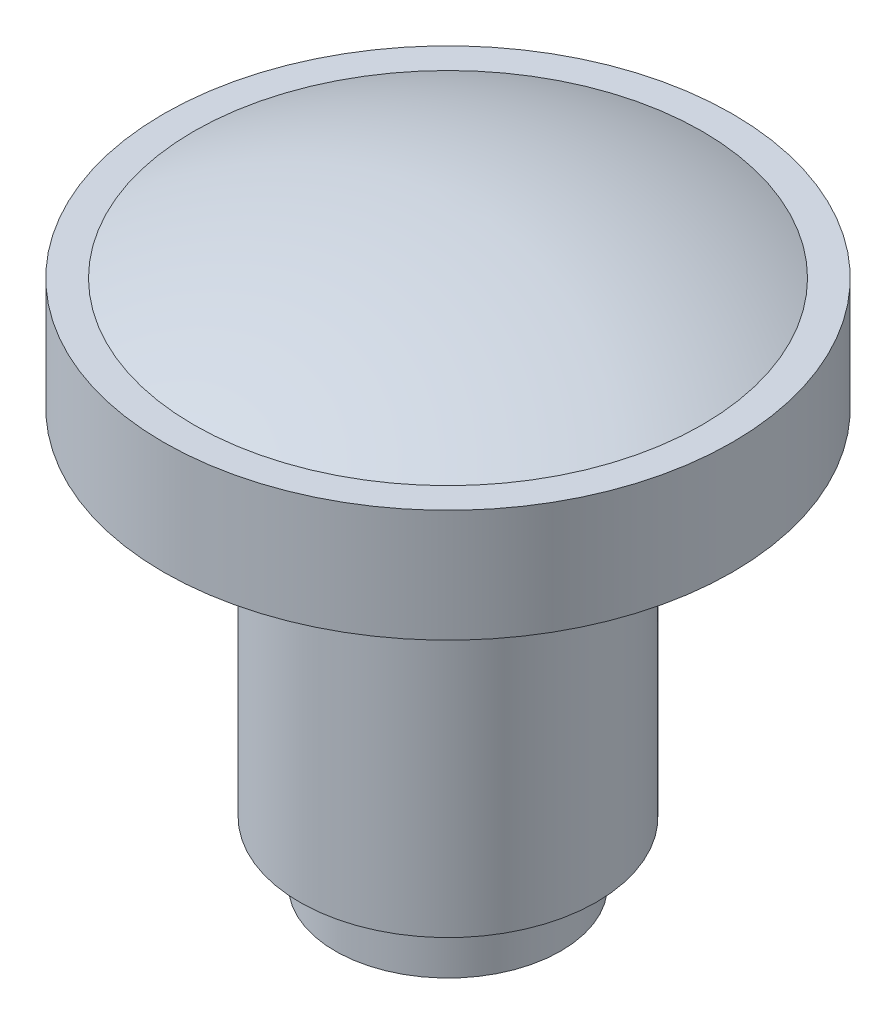
SolidWorks part; units mm, degrees
material "Alliage 1060"
ref_plane "Plan de face" through (0, 0, 0) normal (0, 0, 1) x (1, 0, 0)
ref_plane "Plan de dessus" through (0, 0, 0) normal (0, 1, 0) x (1, 0, 0)
ref_plane "Plan de droite" through (0, 0, 0) normal (1, 0, 0) x (0, 0, -1)
sketch "Esquisse1" plane through (0, 0, 0) normal (0, 0, 1) x (1, 0, 0)
  line L0 (0, 0) -> (0, 52.6939) construction
  line L1 (14.75, 0) -> (14.75, 30)
  line L2 (14.75, 30) -> (28.25, 35.1289)
  line L3 (28.25, 35.1289) -> (28.25, 46.3)
  line L4 (28.25, 46.3) -> (0, 46.3) construction
  line L5 (0, 46.3) -> (0, -5.9868)
  line L6 (0, -5.9868) -> (11.2036, -5.9868)
  line L7 (11.2036, -5.9868) -> (11.2036, 0)
  line L8 (11.2036, 0) -> (14.75, 0)
  line L9 (0, 52.1) -> (14.0132, 52.1) construction
  line L10 (25.25, 46.3) -> (28.25, 46.3)
  line L11 (0, 46.3) -> (0, 52.1)
  arc A0 (25.25, 46.3) -> (0, 52.1) centre (0, -5.7623) ccw
  dimension "D5" = 52.1
  dimension "D1" = 14.75
  dimension "D2" = 28.25
  dimension "D3" = 46.3
  dimension "D4" = 30
  dimension "D6" = 3
revolve "Révolution1" add sketch "Esquisse1" angle 360 about L11
